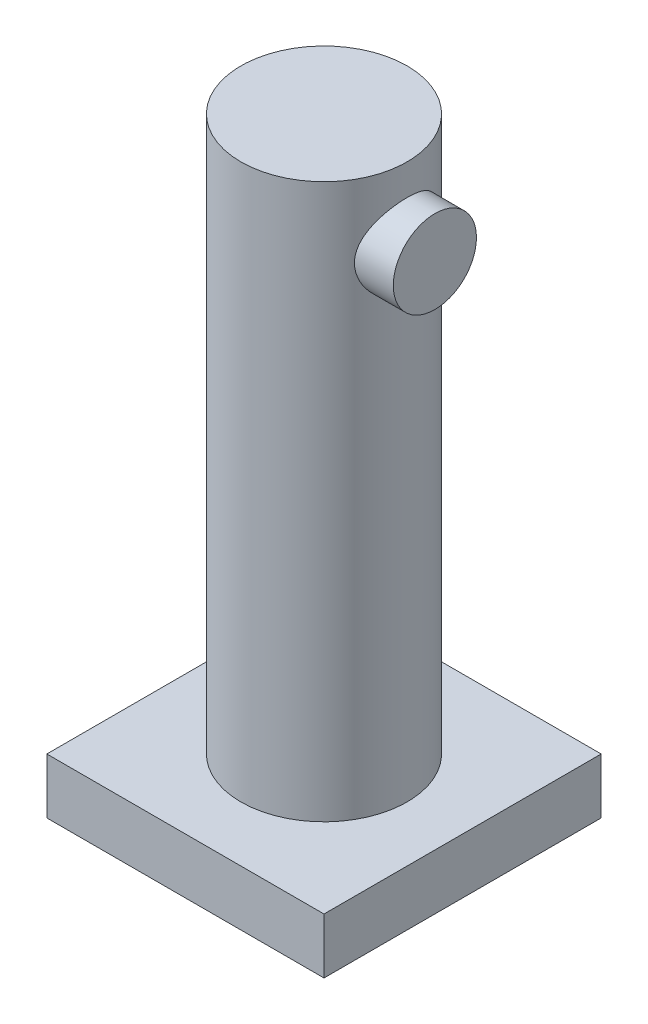
SolidWorks part; units mm, degrees
ref_plane "Alzado" through (0, 0, 0) normal (0, 0, 1) x (1, 0, 0)
ref_plane "Planta" through (0, 0, 0) normal (0, 1, 0) x (1, 0, 0)
ref_plane "Vista lateral" through (0, 0, 0) normal (1, 0, 0) x (0, 0, -1)
sketch "Croquis2" plane through (0, 0, 0) normal (0, 1, 0) x (1, 0, 0)
  line L1 (-250, 250) -> (250, 250)
  line L2 (-250, 250) -> (-250, -250)
  line L3 (-250, -250) -> (250, -250)
  line L4 (250, 250) -> (250, -250)
  line L5 (-250, 250) -> (250, -250) construction
  line L6 (-250, -250) -> (250, 250) construction
  point P0 (0, 0)
  dimension "D1" = 500
  dimension "D2" = 500
extrude "Saliente-Extruir1" add sketch "Croquis2" along normal blind 100
sketch "Croquis3" plane through (0, 100, 0) normal (0, 1, 0) x (1, 0, 0)
  circle A0 centre (0, 0) radius 150
  dimension "D1" = 300
extrude "Saliente-Extruir2" add sketch "Croquis3" along normal blind 1000
sketch "Croquis5" plane through (0, 0, 0) normal (1, 0, 0) x (0, 0, -1)
  circle A0 centre (0, 969.2656) radius 75
  dimension "D1" = 150
extrude "Saliente-Extruir4" add sketch "Croquis5" along normal blind 200
